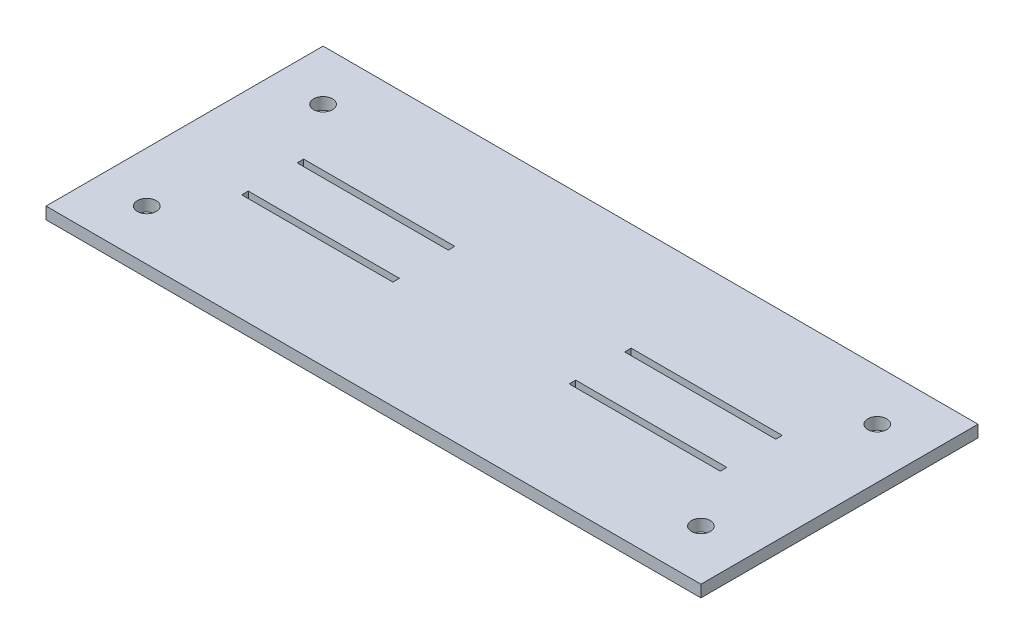
SolidWorks part; units mm, degrees
material "Thornel VCB-20 Carbon Cloth"
ref_plane "Front Plane" through (0, 0, 0) normal (0, 0, 1) x (1, 0, 0)
ref_plane "Top Plane" through (0, 0, 0) normal (0, 1, 0) x (1, 0, 0)
ref_plane "Right Plane" through (0, 0, 0) normal (1, 0, 0) x (0, 0, -1)
sketch "Sketch1" plane through (0, 0, 0) normal (0, 1, 0) x (1, 0, 0)
  line L0 (82.55, -34.925) -> (82.55, 34.925)
  line L1 (82.55, -34.925) -> (-82.55, -34.925)
  line L2 (82.55, 34.925) -> (-82.55, 34.925)
  line L3 (-82.55, -34.925) -> (-82.55, 34.925)
  line L4 (82.55, -34.925) -> (-82.55, 34.925) construction
  line L5 (82.55, 34.925) -> (-82.55, -34.925) construction
  point P1 (0, 0)
  dimension "D1" = 165.1
  dimension "D2" = 69.85
extrude "Boss-Extrude1" add sketch "Sketch1" along normal blind 3
sketch "Sketch6" plane through (0, 0, 0) normal (0, -1, 0) x (1, 0, 0)
  line L0 (-82.55, -34.925) -> (-82.55, 34.925) construction
  line L1 (-69.85, 5) -> (-34.925, 5)
  line L2 (-69.85, 5) -> (-69.85, -5)
  line L3 (-69.85, -5) -> (-34.925, -5)
  line L4 (-34.925, 5) -> (-34.925, -5)
  circle A0 centre (-15.25, 15.25) radius 1.5
  circle A1 centre (15.25, 15.25) radius 1.5
  circle A2 centre (-15.25, -15.25) radius 1.5
  circle A3 centre (15.25, -15.25) radius 1.5
  point P8 (-34.925, 0)
  dimension "D5" = 3
  dimension "D6" = 3
  dimension "D7" = 3
  dimension "D8" = 3
  dimension "D1" = 34.925
  dimension "D2" = 10
  dimension "D3" = 12.7
  dimension "D9" = 15.25
  dimension "D10" = 15.25
  dimension "D11" = 15.25
  dimension "D12" = 15.25
  dimension "D13" = 15.25
  dimension "D14" = 15.25
  dimension "D15" = 15.25
  dimension "D16" = 15.25
sketch "Sketch8" plane through (0, 3, 0) normal (0, 1, 0) x (1, 0, 0)
  line L0 (-82.55, -34.925) -> (82.55, -34.925) construction
  line L1 (-82.55, 34.925) -> (-82.55, -34.925) construction
  line L2 (82.55, -34.925) -> (82.55, 34.925) construction
  line L3 (82.55, 34.925) -> (-82.55, 34.925) construction
  circle A0 centre (-69.85, -22.225) radius 2.3813
  circle A1 centre (-69.85, 22.225) radius 2.3813
  circle A2 centre (69.85, 22.225) radius 2.3813
  circle A3 centre (69.85, -22.225) radius 2.3813
  dimension "D1" = 4.7625
  dimension "D4" = 4.7625
  dimension "D5" = 4.7625
  dimension "D6" = 4.7625
  dimension "D2" = 12.7
  dimension "D3" = 12.7
  dimension "D7" = 12.7
  dimension "D8" = 12.7
  dimension "D9" = 12.7
  dimension "D10" = 12.7
  dimension "D11" = 12.7
  dimension "D12" = 12.7
extrude "Cut-Extrude3" cut sketch "Sketch8" against normal up to next
sketch "Sketch10" plane through (0, 0, 0) normal (0, -1, 0) x (1, 0, 0)
  line L0 (0, 0) -> (-82.55, 0) construction
  line L1 (-82.55, -34.925) -> (-82.55, 34.925) construction
  line L2 (-60.325, -6.985) -> (-22.225, -6.985) construction
  line L3 (-60.325, -6.1595) -> (-22.225, -6.1595)
  line L4 (-60.325, -6.1595) -> (-60.325, -7.8105)
  line L5 (-60.325, -7.8105) -> (-22.225, -7.8105)
  line L6 (-22.225, -6.1595) -> (-22.225, -7.8105)
  line L7 (-60.325, 7.8105) -> (-22.225, 7.8105)
  line L8 (-22.225, 6.1595) -> (-22.225, 7.8105)
  line L9 (-60.325, 6.1595) -> (-22.225, 6.1595)
  line L10 (-60.325, 6.1595) -> (-60.325, 7.8105)
  line L11 (60.325, 6.1595) -> (22.225, 6.1595)
  line L12 (60.325, 6.1595) -> (60.325, 7.8105)
  line L13 (60.325, 7.8105) -> (22.225, 7.8105)
  line L14 (22.225, 6.1595) -> (22.225, 7.8105)
  line L15 (60.325, -7.8105) -> (22.225, -7.8105)
  line L16 (22.225, -6.1595) -> (22.225, -7.8105)
  line L17 (60.325, -6.1595) -> (22.225, -6.1595)
  line L18 (60.325, -6.1595) -> (60.325, -7.8105)
  line L19 (60.325, 6.985) -> (22.225, 6.985) construction
  point P11 (-41.275, -6.985)
  point P28 (0, 0)
  dimension "D1" = 1.651
  dimension "D2" = 38.1
  dimension "D3" = 6.985
  dimension "D4" = 22.225
  dimension "D5" = 2
extrude "Cut-Extrude4" cut sketch "Sketch10" against normal blind 26.67
